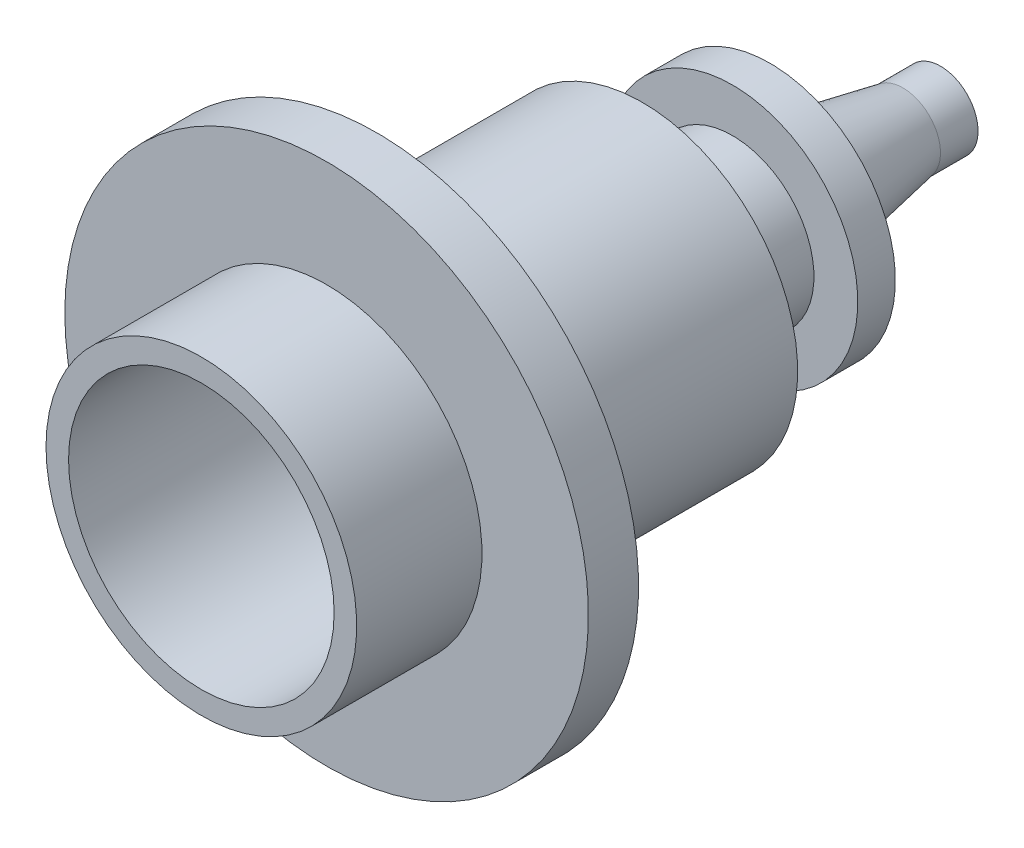
SolidWorks part; units mm, degrees
ref_plane "Top" through (0, 0, 0) normal (0, 0, 1) x (1, 0, 0)
ref_plane "Front" through (0, 0, 0) normal (0, 1, 0) x (1, 0, 0)
ref_plane "Right" through (0, 0, 0) normal (1, 0, 0) x (0, 0, -1)
sketch "Body Sketch" plane through (0, 0, 0) normal (0, 1, 0) x (1, 0, 0)
  line L0 (0, 0) -> (0, -14.75) construction
  line L2 (2.65, -14.75) -> (3.1, -14.75)
  line L3 (3.1, -14.75) -> (3.1, -12.25)
  line L4 (3.1, -12.25) -> (5.225, -12.25)
  line L5 (5.225, -12.25) -> (5.225, -11.25)
  line L6 (5.225, -11.25) -> (3.1, -11.25)
  line L7 (3.1, -11.25) -> (3.1, -5.95)
  line L8 (3.1, -5.95) -> (1.625, -5.55)
  line L9 (1.625, -5.55) -> (1.625, -4.15)
  line L10 (1.625, -4.15) -> (2.5, -4.15)
  line L11 (2.5, -4.15) -> (2.5, -3.4)
  line L12 (2.5, -3.4) -> (0.25, -3.4)
  line L17 (0.25, -3.4) -> (0.25, -5.9542)
  line L18 (0.25, -5.9542) -> (2.65, -6.6051)
  line L19 (2.65, -6.6051) -> (2.65, -14.75)
  dimension "D1" = 0.25
  dimension "D3" = 2.5
  dimension "D4" = 0.75
  dimension "D10" = 1.625
  dimension "D11" = 1.4
  dimension "D12" = 0.4
  dimension "D13" = 3.1
  dimension "D14" = 5.225
  dimension "D15" = 1
  dimension "D16" = 2.5
  dimension "D17" = 2.65
  dimension "D18" = 0.75
  dimension "Tip Length" = 3.4
  dimension "D2" = 11.35
revolve "Body Revolve" add sketch "Body Sketch" angle 360 about L0
sketch "N045 Sketch" plane through (0, 0, 0) normal (0, 1, 0) x (1, 0, 0)
  line L0 (0, 0) -> (0, -3.4) construction
  line L4 (1.25, -3.4) -> (0.25, -3.4)
  line L5 (1.25, -3.4) -> (1, -0.75)
  line L6 (1, -0.75) -> (0.78, -0.75)
  line L7 (0.78, -0.75) -> (0.78, 0)
  line L8 (0.78, 0) -> (0.25, 0)
  line L9 (0.25, 0) -> (0.25, -3.4)
  point P2 (0.515, 0)
  dimension "D1" = 1.25
  dimension "D2" = 0.75
  dimension "D4" = 0.25
  dimension "D5" = 0.78
  dimension "D6" = 1
  dimension "Tip Length" = 3.4
revolve "N045 Revolve" [suppressed] add sketch "N045 Sketch" angle 360 about L0
sketch "N08 Sketch" plane through (0, 0, 0) normal (0, 1, 0) x (1, 0, 0)
  line L0 (0.5, 0) -> (0.75, 0)
  line L1 (0.75, 0) -> (0.75, -0.75)
  line L2 (0.75, -0.75) -> (1.25, -3.4)
  line L3 (1.25, -3.4) -> (0.5, -3.4)
  line L4 (0.5, -3.4) -> (0.5, 0)
  line L5 (0, 0) -> (0, -3.4) construction
  dimension "D1" = 3.4
  dimension "D2" = 0.75
  dimension "D3" = 0.5
  dimension "D4" = 0.75
  dimension "D5" = 1.25
revolve "N08 Revolve" add sketch "N08 Sketch" angle 360 about L5
sketch "N14 Sketch" plane through (0, 0, 0) normal (0, 1, 0) x (1, 0, 0)
  line L0 (0.7, 0) -> (1.125, 0)
  line L1 (1.125, 0) -> (1.125, -2.25)
  line L2 (1.125, -2.25) -> (1.25, -3.4)
  line L3 (1.25, -3.4) -> (0.7, -3.4)
  line L4 (0.7, -3.4) -> (0.7, 0)
  line L5 (0, 0) -> (0, -3.4) construction
  dimension "D1" = 0.7
  dimension "D2" = 1.125
  dimension "D3" = 1.25
  dimension "D4" = 2.25
  dimension "Tip Length" = 3.4
revolve "N14 Revolve" [suppressed] add sketch "N14 Sketch" angle 360 about L5
sketch "N24 Sketch" plane through (0, 0, 0) normal (0, 1, 0) x (1, 0, 0)
  line L0 (1.2, 0) -> (2, 0)
  line L1 (2, 0) -> (2, -3.4)
  line L3 (2, -3.4) -> (1.2, -3.4)
  line L4 (1.2, -3.4) -> (1.2, 0)
  line L5 (0, 0) -> (0, -3.4) construction
  dimension "D3" = 1.2
  dimension "D4" = 2
  dimension "Tip Length" = 3.4
revolve "N24 Revolve" [suppressed] add sketch "N24 Sketch" angle 360 about L5
sketch "N40 Sketch" [suppressed] plane through (0, 0, 0) normal (0, 1, 0) x (1, 0, 0)
  line L0 (2, 0) -> (3.1, 0)
  line L1 (3.1, 0) -> (3.1, -3.4)
  line L3 (3.1, -3.4) -> (2, -3.4)
  line L4 (2, -3.4) -> (2, 0)
  line L5 (0, 0) -> (0, -3.4) construction
  dimension "D1" = 3.4
  dimension "D3" = 2
  dimension "D4" = 3.1
revolve "N40 Revolve" [suppressed] add sketch "N40 Sketch" angle 360 about L5
sketch "N75 Sketch" [suppressed] plane through (0, 0, 0) normal (0, 1, 0) x (1, 0, 0)
  line L0 (3.75, 0) -> (4.5, 0)
  line L1 (4.5, 0) -> (4.5, -3.4)
  line L3 (4.5, -3.4) -> (0.8, -3.4)
  line L4 (3.75, -2.65) -> (3.75, 0)
  line L5 (0, 0) -> (0, -3.4) construction
  line L6 (0.8, -2.65) -> (3.75, -2.65)
  line L7 (0.8, -2.65) -> (0.8, -3.4)
  dimension "D1" = 3.4
  dimension "D2" = 0.8
  dimension "D3" = 3.75
  dimension "D4" = 4.5
  dimension "D5" = 0.75
revolve "N75 Revolve" [suppressed] add sketch "N75 Sketch" angle 360 about L5
equation "\"D10@Body Sketch\" = 3.25 / 2"
